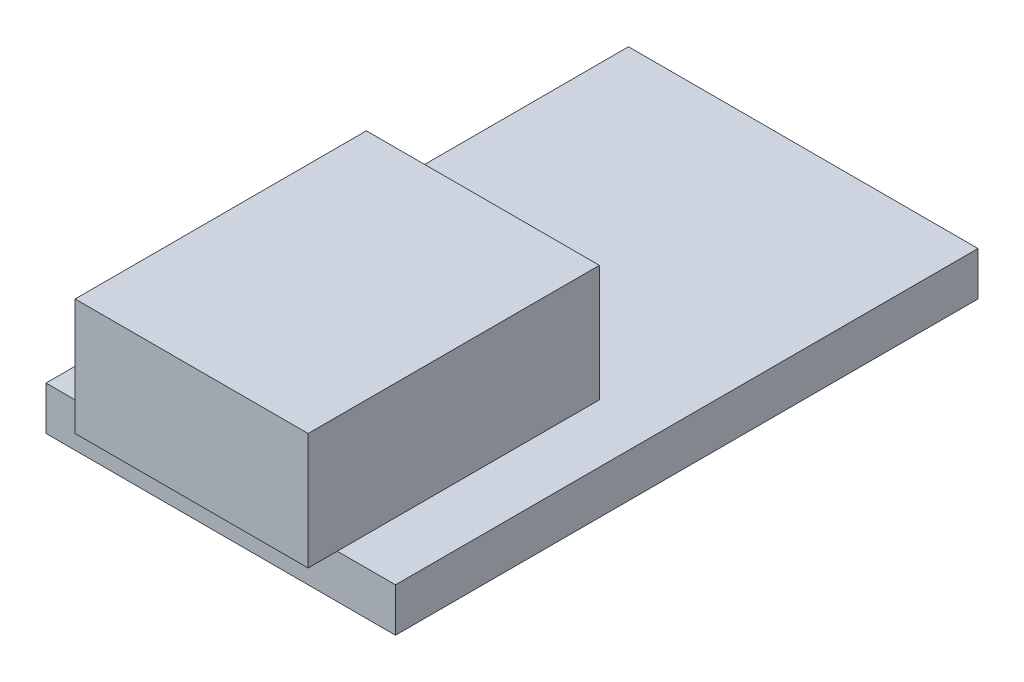
SolidWorks part; units mm, degrees
ref_plane "Front Plane" through (0, 0, 0) normal (0, 0, 1) x (1, 0, 0)
ref_plane "Top Plane" through (0, 0, 0) normal (0, 1, 0) x (1, 0, 0)
ref_plane "Right Plane" through (0, 0, 0) normal (1, 0, 0) x (0, 0, -1)
sketch "Sketch1" plane through (0, 0, 0) normal (0, 1, 0) x (1, 0, 0)
  line L1 (-4, -5) -> (4, -5)
  line L2 (-4, -5) -> (-4, 5)
  line L3 (-4, 5) -> (4, 5)
  line L4 (4, -5) -> (4, 5)
  line L5 (-4, -5) -> (4, 5) construction
  line L6 (-4, 5) -> (4, -5) construction
  point P0 (0, 0)
  dimension "D1" = 8
  dimension "D2" = 10
extrude "Boss-Extrude1" add sketch "Sketch1" along normal blind 4
sketch "Sketch2" plane through (0, 0, 0) normal (0, -1, 0) x (1, 0, 0)
  line L0 (-4, 5) -> (4, 5) construction
  line L1 (6, 4) -> (-6, 4)
  line L2 (6, 4) -> (6, -16)
  line L3 (6, -16) -> (-6, -16)
  line L4 (-6, 4) -> (-6, -16)
  line L5 (-4, -5) -> (-4, 5) construction
  dimension "D1" = 1
  dimension "D2" = 12
  dimension "D3" = 2
  dimension "D4" = 20
extrude "Boss-Extrude2" add sketch "Sketch2" along normal blind 1.5
